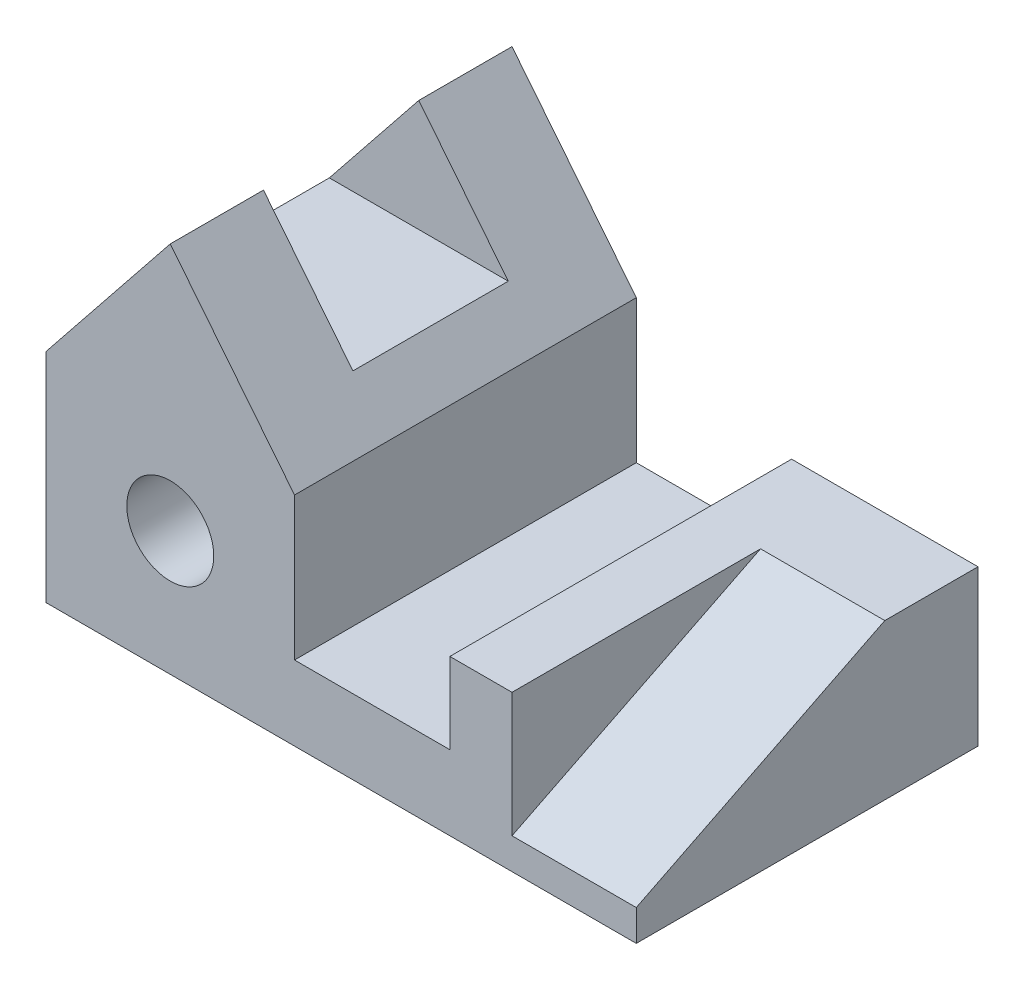
SolidWorks part; units mm, degrees
ref_plane "Plano frontal" through (0, 0, 0) normal (0, 0, 1) x (1, 0, 0)
ref_plane "Plano superior" through (0, 0, 0) normal (0, 1, 0) x (1, 0, 0)
ref_plane "Plano direito" through (0, 0, 0) normal (1, 0, 0) x (0, 0, -1)
sketch "Esboço1" plane through (0, 0, 0) normal (0, 0, 1) x (1, 0, 0)
  line L0 (-86.063, 1.2565) -> (-86.063, 36.2565)
  line L1 (-86.063, 36.2565) -> (-66.063, 61.2565)
  line L2 (-66.063, 61.2565) -> (-46.063, 36.2565)
  line L3 (-46.063, 36.2565) -> (-46.063, 13.2565)
  line L4 (-46.063, 13.2565) -> (-21.063, 13.2565)
  line L5 (-21.063, 13.2565) -> (-21.063, 26.2565)
  line L6 (-21.063, 26.2565) -> (8.937, 26.2565)
  line L7 (8.937, 26.2565) -> (8.937, 1.2565)
  line L8 (8.937, 1.2565) -> (-86.063, 1.2565)
  circle A0 centre (-66.063, 21.2565) radius 7
  point P11 (-52.2466, 34.2713)
  point P12 (0, 0)
  point P13 (-66.063, 34.8761)
  point P14 (0, 0)
  point P15 (0, 0)
  dimension "D1" = 14
  dimension "D2" = 60
  dimension "D3" = 20
  dimension "D4" = 35
  dimension "D5" = 12
  dimension "D6" = 30
  dimension "D7" = 25
  dimension "D8" = 25
  dimension "D9" = 20
extrude "Ressalto-extrusão1" add sketch "Esboço1" against normal blind 55
sketch "Esboço2" plane through (-86.063, 0, 0) normal (-1, 0, 0) x (0, 0, 1)
  line L0 (-40, 61.2565) -> (-40, 43.2565)
  line L1 (-55, 61.2565) -> (0, 61.2565) construction
  line L2 (-40, 43.2565) -> (-15, 43.2565)
  line L3 (-15, 43.2565) -> (-15, 61.2565)
  line L4 (-15, 61.2565) -> (-40, 61.2565)
  line L5 (-55, 61.2565) -> (-55, 36.2565) construction
  line L6 (0, 61.2565) -> (0, 36.2565) construction
  dimension "D1" = 15
  dimension "D2" = 18
  dimension "D3" = 15
extrude "Corte-extrusão1" cut sketch "Esboço2" against normal up to next
sketch "Esboço3" plane through (8.937, 0, 0) normal (1, 0, 0) x (0, 0, -1)
  line L0 (0, 6.2565) -> (40, 26.2565)
  line L1 (0, 1.2565) -> (0, 26.2565) construction
  line L2 (55, 26.2565) -> (0, 26.2565) construction
  line L3 (0, 26.2565) -> (0, 6.2565)
  line L4 (0, 26.2565) -> (40, 26.2565)
  dimension "D1" = 20
  dimension "D2" = 40
extrude "Corte-extrusão2" cut sketch "Esboço3" against normal blind 20
